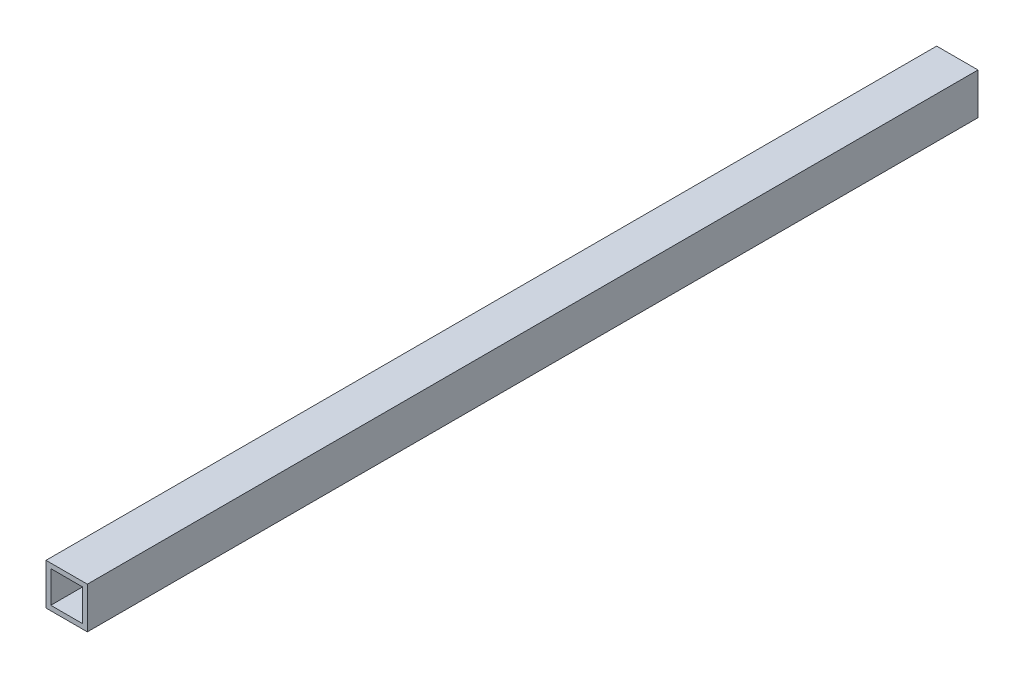
SolidWorks part; units mm, degrees
ref_plane "Front Plane" through (0, 0, 0) normal (0, 0, 1) x (1, 0, 0)
ref_plane "Top Plane" through (0, 0, 0) normal (0, 1, 0) x (1, 0, 0)
ref_plane "Right Plane" through (0, 0, 0) normal (1, 0, 0) x (0, 0, -1)
sketch "Sketch1" plane through (0, 0, 0) normal (0, 0, 1) x (1, 0, 0)
  line L1 (-6.5, 6.5) -> (6.5, 6.5)
  line L2 (-6.5, 6.5) -> (-6.5, -6.5)
  line L3 (-6.5, -6.5) -> (6.5, -6.5)
  line L4 (6.5, 6.5) -> (6.5, -6.5)
  line L5 (-6.5, 6.5) -> (6.5, -6.5) construction
  line L6 (-6.5, -6.5) -> (6.5, 6.5) construction
  line L7 (-5, -5) -> (5, -5)
  line L8 (-5, -5) -> (-5, 5)
  line L9 (-5, 5) -> (5, 5)
  line L10 (5, -5) -> (5, 5)
  line L11 (-5, -5) -> (5, 5) construction
  line L12 (-5, 5) -> (5, -5) construction
  point P0 (0, 0)
  point P6 (0, 0)
  dimension "D1" = 13
  dimension "D2" = 13
  dimension "D3" = 1.5
extrude "Boss-Extrude1" add sketch "Sketch1" along normal blind 280
ref_plane "Plane1" through (0, 0, 140) normal (0, 0, 1) x (1, 0, 0)
